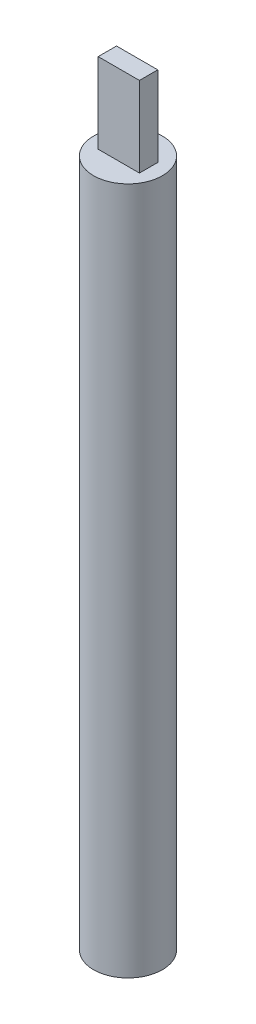
SolidWorks part; units mm, degrees
ref_plane "Front Plane" through (0, 0, 0) normal (0, 0, 1) x (1, 0, 0)
ref_plane "Top Plane" through (0, 0, 0) normal (0, 1, 0) x (1, 0, 0)
ref_plane "Right Plane" through (0, 0, 0) normal (1, 0, 0) x (0, 0, -1)
sketch "Sketch1" plane through (0, 0, 0) normal (0, 1, 0) x (1, 0, 0)
  circle A0 centre (0, 0) radius 15
  dimension "D1" = 30
extrude "Boss-Extrude1" add sketch "Sketch1" along normal blind 300
sketch "Sketch2" plane through (0, 300, 0) normal (0, 1, 0) x (1, 0, 0)
  line L1 (9, -4) -> (-9, -4)
  line L2 (9, -4) -> (9, 4)
  line L3 (9, 4) -> (-9, 4)
  line L4 (-9, -4) -> (-9, 4)
  line L5 (9, -4) -> (-9, 4) construction
  line L6 (9, 4) -> (-9, -4) construction
  point P0 (0, 0)
  dimension "D1" = 18
  dimension "D2" = 8
extrude "Boss-Extrude2" add sketch "Sketch2" along normal blind 35
